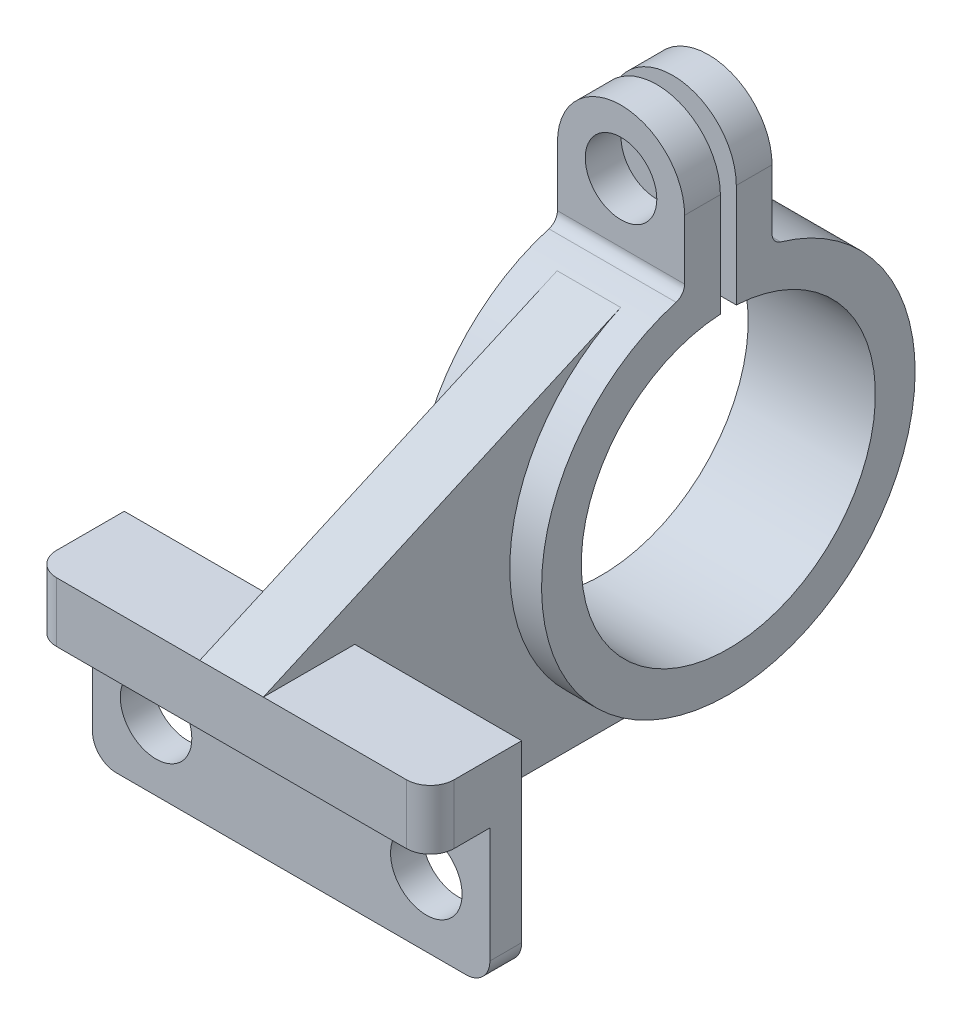
SolidWorks part; units mm, degrees
other "中間"
ref_plane "前基準面" through (0, 0, 0) normal (0, 0, 1) x (1, 0, 0)
ref_plane "上基準面" through (0, 0, 0) normal (0, 1, 0) x (1, 0, 0)
ref_plane "右基準面" through (0, 0, 0) normal (1, 0, 0) x (0, 0, -1)
sketch "控制草圖" plane through (0, 0, 0) normal (1, 0, 0) x (0, 0, -1)
  line L1 (0, 0) -> (0, -47) construction
  line L2 (0, -47) -> (-94, -47) construction
  line L3 (-94, -47) -> (-94, 3) construction
  circle A0 centre (0, 0) radius 37
  circle A1 centre (0, 0) radius 47
  dimension "D1" = 74
  dimension "D2" = 94
  dimension "D3" = 94
  dimension "D5" = 50
sketch "草圖2" plane through (0, 0, 0) normal (1, 0, 0) x (0, 0, -1)
  circle A0 centre (0, 0) radius 47
  circle A1 centre (0, 0) radius 47 construction
  circle A2 centre (0, 0) radius 37
  circle A3 centre (0, 0) radius 37 construction
extrude "底部圓" add sketch "草圖2" along normal mid plane 32
sketch "草圖3" plane through (0, 0, 0) normal (0, 0, 1) x (1, 0, 0)
  line L0 (0, 0) -> (0, 63) construction
  line L1 (16, 37) -> (-16, 37)
  line L3 (-16, 37) -> (-16, 63)
  line L4 (16, 63) -> (16, 37)
  arc A0 (-16, 63) -> (16, 63) centre (0, 63) cw
  circle A1 centre (0, 63) radius 9
  dimension "D2" = 32
  dimension "D4" = 18
  dimension "D1" = 63
  dimension "D3" = 26
extrude "上部圓" add sketch "草圖3" along normal mid plane 22
sketch "草圖6" plane through (0, 0, 0) normal (1, 0, 0) x (0, 0, -1)
  line L0 (0, 0) -> (0, 44) construction
  line L7 (2, 36.9459) -> (2, 81.9459)
  line L8 (2, 81.9459) -> (-2, 81.9459)
  line L9 (-2, 81.9459) -> (-2, 36.9459)
  line L10 (-2, 36.9459) -> (2, 36.9459)
  circle A1 centre (0, 0) radius 37 construction
  point P11 (0, 36.9459)
  dimension "D1" = 4
  dimension "D2" = 45
extrude "除料-伸長1" cut sketch "草圖6" against normal mid plane 32
fillet "圓角1" radius 3 2 edges at (0, 45.6946, -11) (0, 45.6946, 11)
sketch "草圖14" plane through (0, 0, 0) normal (1, 0, 0) x (0, 0, -1)
  line L6 (-94, -47) -> (-86, -47)
  line L7 (-86, -47) -> (-86, 3)
  line L8 (-86, 3) -> (-109, 3)
  line L9 (-109, 3) -> (-109, -12)
  line L10 (-109, -12) -> (-94, -12)
  line L11 (-94, -12) -> (-94, -47)
  dimension "D1" = 23
  dimension "D2" = 8
  dimension "D3" = 15
extrude "左支架" add sketch "草圖14" along normal mid plane 100 separate body
sketch "草圖18" plane through (0, 0, 94) normal (0, 0, 1) x (1, 0, 0)
  line L0 (-34, -30) -> (34, -30) construction
  line L1 (0, -47) -> (0, 47) construction
  line L3 (50, -47) -> (-50, -47) construction
  circle A0 centre (-34, -30) radius 9
  circle A1 centre (34, -30) radius 9
  point P4 (0, -30)
  dimension "D1" = 18
  dimension "D2" = 18
  dimension "D3" = 17
  dimension "D4" = 68
extrude "圓洞" cut sketch "草圖18" against normal up to next (8 mm away)
fillet "圓角3" radius 6 4 edges at (50, -47, 90) (-50, -47, 90) (-50, -4.5, 109) (50, -4.5, 109)
sketch "草圖20" plane through (0, 0, 0) normal (1, 0, 0) x (0, 0, -1)
  line L0 (-109, 3) -> (-19.0839, 42.9512)
  line L1 (0, -47) -> (-86, -47)
  line L2 (0, -47) -> (-94, -47) construction
  line L3 (-86, -47) -> (-86, 3)
  line L4 (-86, 3) -> (-109, 3)
  circle A0 centre (0, 0) radius 47 construction
  arc A1 (-19.0839, 42.9512) -> (0, -47) centre (0, 0) ccw
  dimension "D2" = 47
  dimension "D1" = 8
extrude "連接" add sketch "草圖20" along normal mid plane 16
